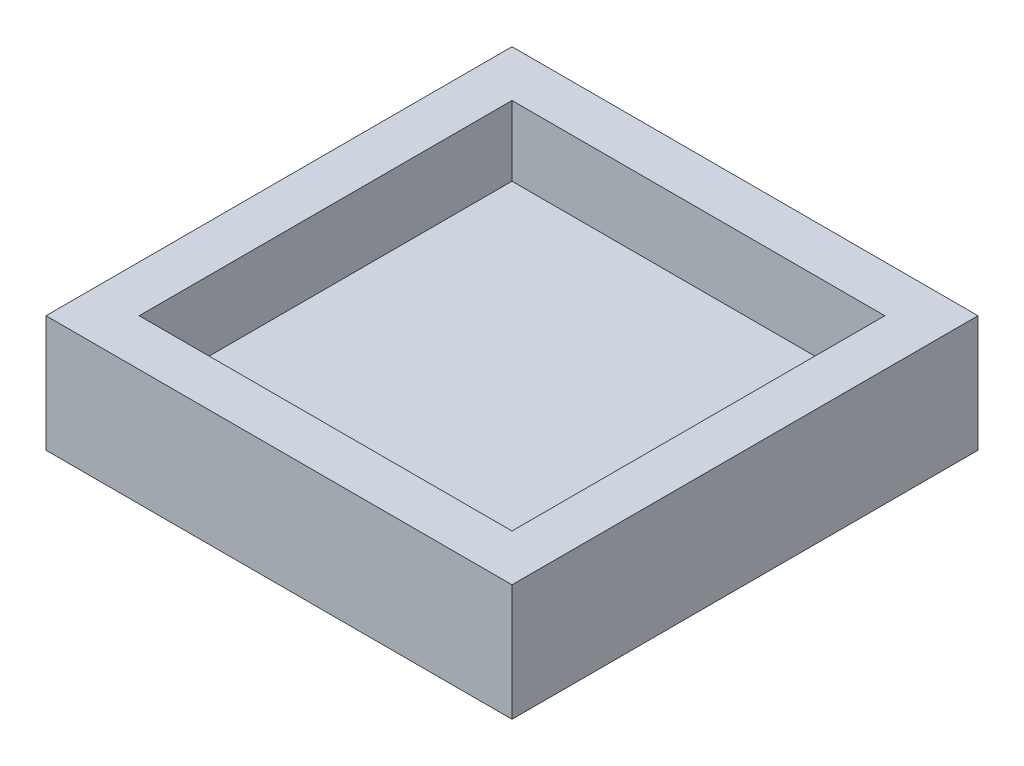
SolidWorks part; units mm, degrees
ref_plane "Front Plane" through (0, 0, 0) normal (0, 0, 1) x (1, 0, 0)
ref_plane "Top Plane" through (0, 0, 0) normal (0, 1, 0) x (1, 0, 0)
ref_plane "Right Plane" through (0, 0, 0) normal (1, 0, 0) x (0, 0, -1)
sketch "Sketch2" plane through (0, 0, 0) normal (0, 1, 0) x (1, 0, 0)
  line L1 (0, 0) -> (25.4, 0)
  line L2 (0, 0) -> (0, 25.4)
  line L3 (0, 25.4) -> (25.4, 25.4)
  line L4 (25.4, 0) -> (25.4, 25.4)
  dimension "D1" = 25.4
  dimension "D2" = 25.4
extrude "Boss-Extrude1" add sketch "Sketch2" along normal blind 6.35 contours L2 L3 L4 L1
shell "Shell2" thickness 2.54
